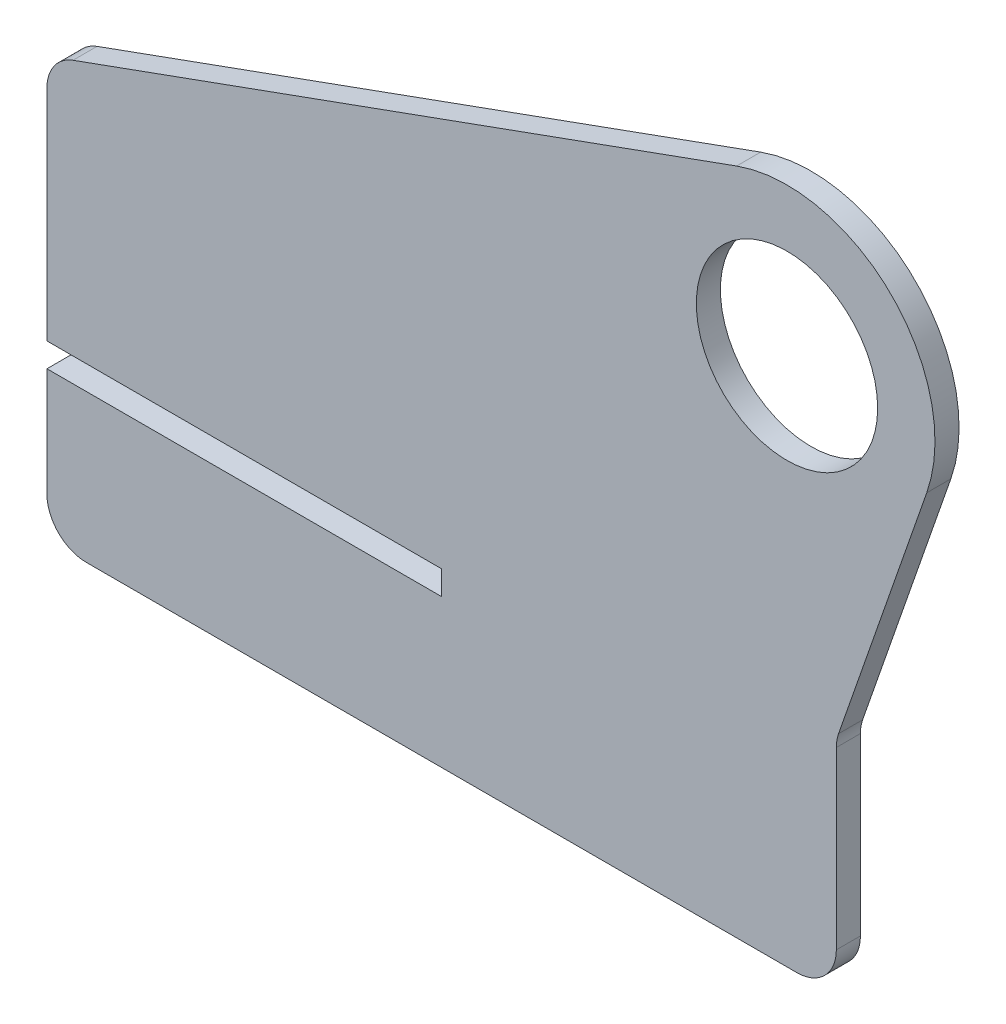
SolidWorks part; units mm, degrees
material "Corrugated Paper"
ref_plane "Front Plane" through (0, 0, 0) normal (0, 0, 1) x (1, 0, 0)
ref_plane "Top Plane" through (0, 0, 0) normal (0, 1, 0) x (1, 0, 0)
ref_plane "Right Plane" through (0, 0, 0) normal (1, 0, 0) x (0, 0, -1)
sketch "Sketch2" plane through (0, 0, 0) normal (0, 0, 1) x (1, 0, 0)
  line L0 (-50.8, 1.5494) -> (-50.8, 7.8994)
  line L1 (-50.8, -7.8994) -> (50.8, -7.8994)
  line L2 (-50.8, -7.8994) -> (-50.8, -1.5494)
  line L3 (-50.8, 7.8994) -> (50.8, 7.8994)
  line L4 (50.8, -7.8994) -> (50.8, 7.8994)
  line L5 (-50.8, -7.8994) -> (50.8, 7.8994) construction
  line L6 (-50.8, 7.8994) -> (50.8, -7.8994) construction
  line L7 (-50.8, 1.5494) -> (0, 1.5494)
  line L9 (-50.8, -1.5494) -> (0, -1.5494)
  line L10 (0, 1.5494) -> (0, -1.5494)
  point P0 (0, 0)
  dimension "D1" = 50.8
  dimension "D3" = 3.0988
  dimension "D2" = 6.35
extrude "Boss-Extrude1" add sketch "Sketch2" along normal blind 3.0988
sketch "Sketch3" plane through (0, 0, 0) normal (0, 0, 1) x (1, 0, 0)
  line L0 (-50.8, -7.8994) -> (-50.8, -20.5994)
  line L1 (-50.8, -20.5994) -> (101.6, -20.5994)
  line L2 (101.6, -20.5994) -> (101.6, 33.2994)
  line L3 (50.8, 7.8994) -> (-50.8, 7.8994) construction
  line L5 (-50.8, 33.2994) -> (-50.8, 7.8994)
  line L6 (-50.8, -7.8994) -> (50.8, -7.8994) construction
  line L7 (50.8, -7.8994) -> (50.8, 7.8994) construction
  line L8 (-50.8, -7.8994) -> (50.8, -7.8994)
  line L9 (50.8, -7.8994) -> (50.8, 7.8994)
  line L10 (50.8, 7.8994) -> (-50.8, 7.8994)
  line L12 (54.7822, 63.5237) -> (101.6, 33.2994)
  line L13 (37.9659, 65.4316) -> (-50.8, 33.2994)
  circle A0 centre (76.2, 0) radius 1.0795
  circle A1 centre (44.45, 47.519) radius 11.6713
  arc A2 (54.7822, 63.5237) -> (37.9659, 65.4316) centre (44.45, 47.519) ccw
  dimension "D1" = 2.159
  dimension "D7" = 38.1
  dimension "D8" = 23.3426
  dimension "D2" = 12.7
  dimension "D3" = 25.4
  dimension "D4" = 152.4
  dimension "D5" = 25.4
  dimension "D6" = 57.15
  dimension "D9" = 31.75
extrude "Boss-Extrude2" add sketch "Sketch3" along normal blind 3.0988
sketch "Sketch4" plane through (0, 0, 3.0988) normal (0, 0, 1) x (1, 0, 0)
  line L0 (62.4362, 41.2421) -> (50.8, 7.8994)
  line L2 (50.8, 7.8994) -> (50.8, -20.5994)
  line L11 (37.9659, 65.4316) -> (-50.8, 33.2994)
  line L12 (-50.8, 33.2994) -> (-50.8, 1.5494)
  line L13 (-50.8, 1.5494) -> (0, 1.5494)
  line L14 (0, 1.5494) -> (0, -1.5494)
  line L15 (0, -1.5494) -> (-50.8, -1.5494)
  line L16 (-50.8, -1.5494) -> (-50.8, -20.5994)
  line L17 (-50.8, -20.5994) -> (101.6, -20.5994)
  line L18 (101.6, -20.5994) -> (101.6, 33.2994)
  line L19 (101.6, 33.2994) -> (54.7822, 63.5237)
  line L20 (37.9659, 65.4316) -> (-50.8, 33.2994)
  line L21 (-50.8, 33.2994) -> (-50.8, 1.5494)
  line L22 (-50.8, 1.5494) -> (0, 1.5494)
  line L23 (0, 1.5494) -> (0, -1.5494)
  line L24 (0, -1.5494) -> (-50.8, -1.5494)
  line L25 (-50.8, -1.5494) -> (-50.8, -20.5994)
  line L26 (-50.8, -20.5994) -> (101.6, -20.5994)
  line L27 (101.6, -20.5994) -> (101.6, 33.2994)
  line L28 (101.6, 33.2994) -> (54.7822, 63.5237)
  circle A1 centre (44.45, 47.519) radius 19.05
  arc A2 (54.7822, 63.5237) -> (37.9659, 65.4316) centre (44.45, 47.519) ccw construction
  arc A4 (54.7822, 63.5237) -> (37.9659, 65.4316) centre (44.45, 47.519) ccw
  arc A5 (54.7822, 63.5237) -> (37.9659, 65.4316) centre (44.45, 47.519) ccw
  dimension "D1" = 0
extrude "Cut-Extrude1" cut sketch "Sketch4" against normal through all
fillet "Fillet1" radius 5.08 4 edges at (-50.8, -20.5994, 1.5494) (-50.8, 33.2994, 1.5494) (50.8, 7.8994, 1.5494) (50.8, -20.5994, 1.5494)
equation "\"rodThick\"= 0.085in"
equation "\"thick\"= 0.122in"
equation "\"clear\"= 0.003in"
equation "\"D3@Sketch2\"=\"thick\""
equation "\"D1@Boss-Extrude1\"=\"thick\""
equation "\"D1@Sketch3\"=\"rodThick\""
equation "\"D1@Boss-Extrude2\"=\"thick\""
equation "\"D8@Sketch3\"=\"MotorDiameter@Motor-1.Part\""
